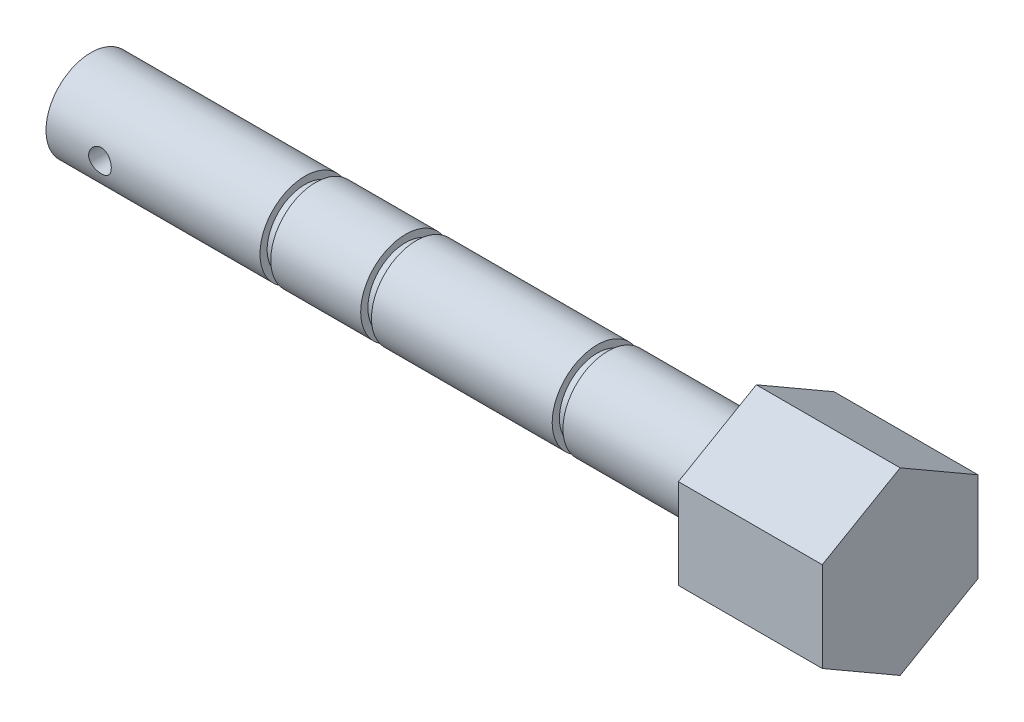
SolidWorks part; units mm, degrees
ref_plane "Front Plane" through (0, 0, 0) normal (0, 0, 1) x (1, 0, 0)
ref_plane "Top Plane" through (0, 0, 0) normal (0, 1, 0) x (1, 0, 0)
ref_plane "Right Plane" through (0, 0, 0) normal (1, 0, 0) x (0, 0, -1)
sketch "Sketch1" plane through (0, 0, 0) normal (1, 0, 0) x (0, 0, -1)
  circle A0 centre (0, 0) radius 3.175
extrude "Boss-Extrude2" add sketch "Sketch1" along normal blind 46.99 contours A0
sketch "Sketch2" plane through (46.99, 0, 0) normal (1, 0, 0) x (0, 0, -1)
  line L1 (-5.4993, 3.175) -> (-5.4993, -3.175)
  line L2 (-5.4993, -3.175) -> (0, -6.35)
  line L3 (0, -6.35) -> (5.4993, -3.175)
  line L4 (5.4993, -3.175) -> (5.4993, 3.175)
  line L5 (5.4993, 3.175) -> (0, 6.35)
  line L6 (0, 6.35) -> (-5.4993, 3.175)
  circle A0 centre (0, 0) radius 5.4993 construction
  dimension "D1" = 6.35
extrude "Boss-Extrude3" add sketch "Sketch2" along normal blind 10.16
sketch "Sketch3" plane through (0, 0, 0) normal (-1, 0, 0) x (0, 0, 1)
  circle A0 centre (0, 0) radius 1.778
  circle A1 centre (0, 0) radius 3.175
extrude "Cut-Extrude1" cut sketch "Sketch3" against normal blind 19.05
sketch "Sketch6" plane through (0, 0, 0) normal (-1, 0, 0) x (0, 0, 1)
  circle A0 centre (0, 0) radius 3.175
extrude "Boss-Extrude5" add sketch "Sketch6" against normal blind 49.022
sketch "Sketch7" plane through (0, 0, 0) normal (-1, 0, 0) x (0, 0, 1)
  line L1 (-0.4893, 0.7146) -> (-0.8635, -0.0664)
  line L2 (-0.8635, -0.0664) -> (-0.3742, -0.781)
  line L3 (-0.3742, -0.781) -> (0.4893, -0.7146)
  line L4 (0.4893, -0.7146) -> (0.8635, 0.0664)
  line L5 (0.8635, 0.0664) -> (0.3742, 0.781)
  line L6 (0.3742, 0.781) -> (-0.4893, 0.7146)
  circle A0 centre (0, 0) radius 0.75 construction
extrude "Cut-Extrude5" cut sketch "Sketch7" against normal blind 38.1
sketch "Sketch9" plane through (0, 0, 0) normal (-1, 0, 0) x (0, 0, 1)
  circle A0 centre (0, 0) radius 0.866
extrude "Cut-Extrude7" cut sketch "Sketch9" against normal blind 46.99 contours A0
sketch "Sketch10" plane through (0, 0, 5.4993) normal (0, 0, 1) x (1, 0, 0)
  line L0 (0, -3.175) -> (46.99, -3.175) construction
  circle A0 centre (3.81, 0) radius 0.8001
  dimension "D1" = 1.6002
  dimension "D2" = 3.81
  dimension "D3" = 3.175
extrude "Cut-Extrude8" cut sketch "Sketch10" against normal blind 5.334 contours A0
ref_plane "Plane1" through (36.5125, 0, 0) normal (-1, 0, 0) x (0, 0, 1)
sketch "Sketch11" plane through (36.5125, 0, 0) normal (-1, 0, 0) x (0, 0, 1)
  circle A0 centre (0, 0) radius 2.667
  circle A1 centre (0, 0) radius 3.175
  dimension "D1" = 5.334
  dimension "D2" = 6.35
extrude "Cut-Extrude9" cut sketch "Sketch11" along normal blind 0.762
ref_plane "Plane2" through (15.875, 0, 0) normal (-1, 0, 0) x (0, 0, 1)
sketch "Sketch12" plane through (15.875, 0, 0) normal (-1, 0, 0) x (0, 0, 1)
  circle A0 centre (0, 0) radius 2.667
  circle A1 centre (0, 0) radius 3.175
  dimension "D1" = 5.334
  dimension "D2" = 6.35
extrude "Cut-Extrude10" cut sketch "Sketch12" along normal blind 0.762
ref_plane "Plane3" through (22.987, 0, 0) normal (-1, 0, 0) x (0, 0, 1)
sketch "Sketch13" plane through (22.987, 0, 0) normal (-1, 0, 0) x (0, 0, 1)
  circle A0 centre (0, 0) radius 2.667
  circle A1 centre (0, 0) radius 3.175
  dimension "D1" = 5.334
  dimension "D2" = 6.35
extrude "Cut-Extrude12" cut sketch "Sketch13" along normal blind 0.762
